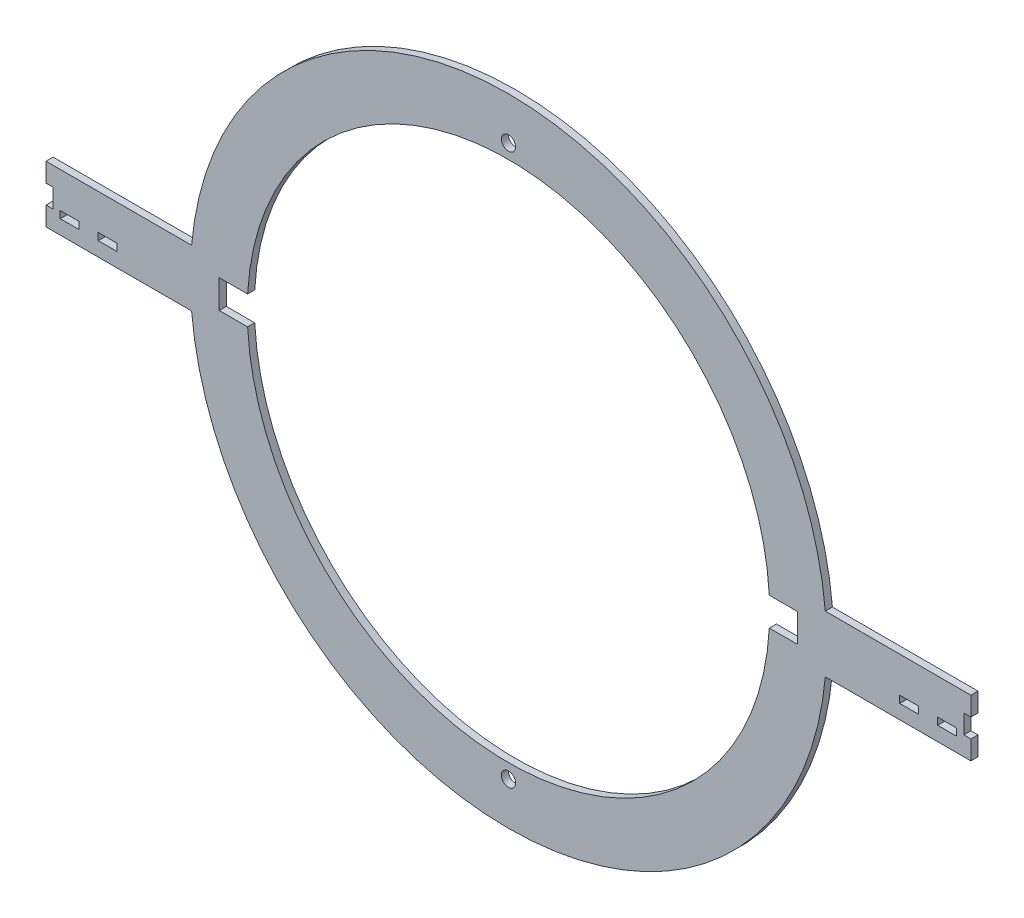
SolidWorks part; units mm, degrees
ref_plane "Front Plane" through (0, 0, 0) normal (0, 0, 1) x (1, 0, 0)
ref_plane "Top Plane" through (0, 0, 0) normal (0, 1, 0) x (1, 0, 0)
ref_plane "Right Plane" through (0, 0, 0) normal (1, 0, 0) x (0, 0, -1)
sketch "Sketch1" plane through (0, 0, 0) normal (0, 0, 1) x (1, 0, 0)
  line L0 (-141.4041, -12.7) -> (-206.375, -12.7)
  line L1 (-206.375, -12.7) -> (-206.375, 12.7)
  line L2 (-206.375, 12.7) -> (-141.4041, 12.7)
  line L3 (0, -55) -> (0, 55) construction
  line L4 (206.375, 12.7) -> (141.4041, 12.7)
  line L5 (206.375, -12.7) -> (206.375, 12.7)
  line L6 (141.4041, -12.7) -> (206.375, -12.7)
  circle A0 centre (0, 0) radius 116.5733
  circle A1 centre (0, 0) radius 141.9733
  point P6 (-206.375, 0)
  dimension "D1" = 233.1466
  dimension "D2" = 25.4
  dimension "D3" = 25.4
  dimension "D4" = 206.375
extrude "Boss-Extrude1" add sketch "Sketch1" along normal blind 3.175 contours A1 L2 L1 L0 | A1 A0 | A1 L6 L5 L4
sketch "Sketch2" plane through (0, 0, 3.175) normal (0, 0, 1) x (1, 0, 0)
  line L0 (-206.375, -12.7) -> (-206.375, 12.7) construction
  line L1 (-206.375, 4.2333) -> (-203.2, 4.2333)
  line L2 (-206.375, 4.2333) -> (-206.375, -4.2333)
  line L3 (-206.375, -4.2333) -> (-203.2, -4.2333)
  line L4 (-203.2, 4.2333) -> (-203.2, -4.2333)
  line L5 (-116.4002, 6.35) -> (-129.1002, 6.35)
  line L6 (-129.1002, 6.35) -> (-129.1002, -6.35)
  line L7 (-129.1002, -6.35) -> (-116.4002, -6.35)
  circle A0 centre (0, 0) radius 116.5733 construction
  arc A2 (-116.4002, 6.35) -> (-116.4002, -6.35) centre (0, 0) ccw
  point P6 (-206.375, 0)
  point P15 (-129.1002, 0)
  dimension "D1" = 8.4667
  dimension "D2" = 3.175
  dimension "D3" = 12.7
  dimension "D4" = 12.7
extrude "Cut-Extrude1" cut sketch "Sketch2" against normal blind 3.175
mirror "Mirror1" about plane through (0, 0, 0) normal (1, 0, 0) of "Cut-Extrude1"
sketch "Sketch3" plane through (0, 0, 3.175) normal (0, 0, 1) x (1, 0, 0)
  circle A0 centre (0, 122.936) radius 3.175
  arc A1 (116.4002, 6.35) -> (-116.4002, 6.35) centre (0, 0) ccw construction
  dimension "D2" = 6.35
  dimension "D1" = 122.936
extrude "Cut-Extrude2" cut sketch "Sketch3" against normal blind 3.175
mirror "Mirror2" about plane through (0, 0, 0) normal (0, 1, 0) of "Cut-Extrude2"
sketch "Sketch4" plane through (0, 0, 3.175) normal (0, 0, 1) x (1, 0, 0)
  line L0 (141.4041, -12.7) -> (206.375, -12.7) construction
  line L1 (200.025, -3.175) -> (191.5583, -3.175)
  line L2 (200.025, -3.175) -> (200.025, -6.35)
  line L3 (200.025, -6.35) -> (191.5583, -6.35)
  line L4 (191.5583, -3.175) -> (191.5583, -6.35)
  line L5 (203.2, -4.2333) -> (203.2, 4.2333) construction
  line L7 (183.0917, -3.175) -> (174.625, -3.175)
  line L8 (183.0917, -3.175) -> (183.0917, -6.35)
  line L9 (183.0917, -6.35) -> (174.625, -6.35)
  line L10 (174.625, -3.175) -> (174.625, -6.35)
  dimension "D1" = 3.175
  dimension "D2" = 6.35
  dimension "D3" = 3.175
  dimension "D4" = 8.4667
  dimension "D5" = 8.4667
extrude "Cut-Extrude3" cut sketch "Sketch4" against normal blind 3.175
mirror "Mirror3" about plane through (0, 0, 0) normal (1, 0, 0) of "Cut-Extrude3"
